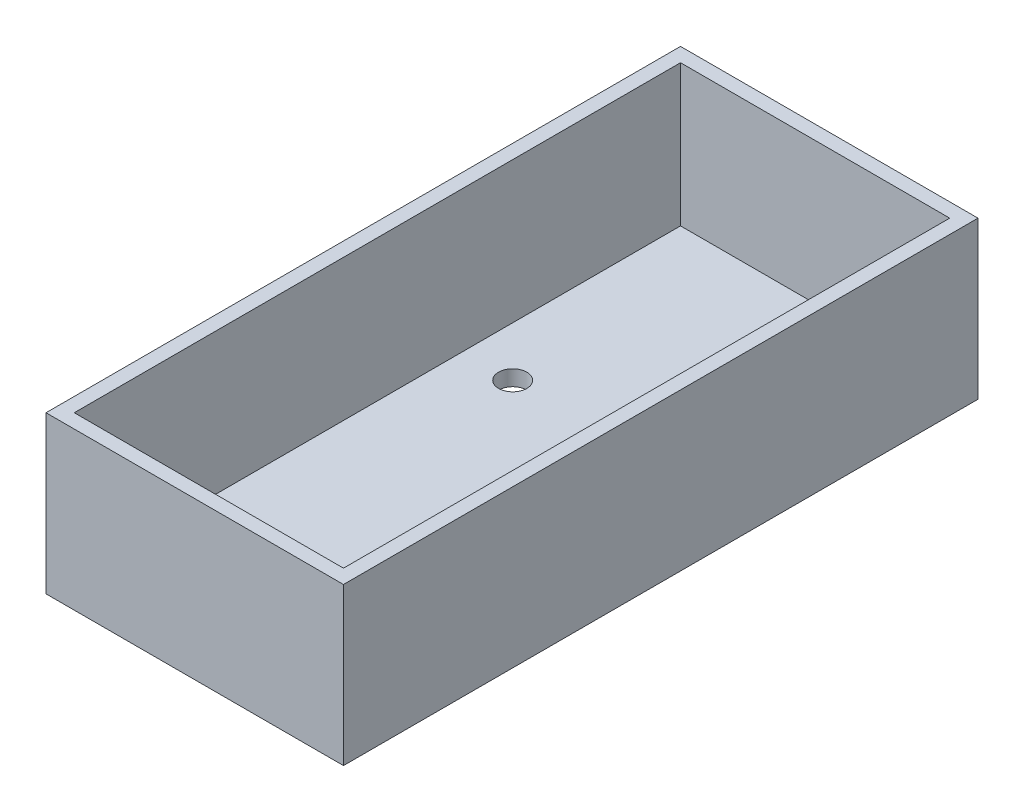
SolidWorks part; units mm, degrees
ref_plane "정면" through (0, 0, 0) normal (0, 0, 1) x (1, 0, 0)
ref_plane "윗면" through (0, 0, 0) normal (0, 1, 0) x (1, 0, 0)
ref_plane "우측면" through (0, 0, 0) normal (1, 0, 0) x (0, 0, -1)
sketch "스케치1" plane through (0, 0, 0) normal (0, 1, 0) x (1, 0, 0)
  line L1 (21.05, -44.9) -> (-21.05, -44.9)
  line L2 (21.05, -44.9) -> (21.05, 44.9)
  line L3 (21.05, 44.9) -> (-21.05, 44.9)
  line L4 (-21.05, -44.9) -> (-21.05, 44.9)
  point P5 (21.05, 0)
  point P8 (0, 44.9)
  dimension "D1" = 89.8
  dimension "D2" = 42.1
extrude "보스-돌출1" add sketch "스케치1" along normal blind 22.2
sketch "스케치2" plane through (0, 22.2, 0) normal (0, 1, 0) x (1, 0, 0)
  line L0 (-21.05, 44.9) -> (-21.05, -44.9) construction
  line L1 (-19.05, 42.9) -> (19.05, 42.9)
  line L2 (-19.05, 42.9) -> (-19.05, -42.9)
  line L3 (-19.05, -42.9) -> (19.05, -42.9)
  line L4 (19.05, 42.9) -> (19.05, -42.9)
  line L5 (-19.05, 42.9) -> (19.05, -42.9) construction
  line L6 (-19.05, -42.9) -> (19.05, 42.9) construction
  line L7 (21.05, 44.9) -> (-21.05, 44.9) construction
  point P0 (0, 0)
  dimension "D1" = 2
  dimension "D2" = 2
extrude "컷-돌출1" cut sketch "스케치2" against normal blind 20
sketch "스케치3" plane through (0, 2.2, 0) normal (0, 1, 0) x (1, 0, 0)
  line L0 (-21.05, -44.9) -> (21.05, -44.9) construction
  line L1 (-12, 12.1) -> (12, 12.1) construction
  line L2 (-12, 12.1) -> (-12, -27.9) construction
  line L3 (-12, -27.9) -> (12, -27.9) construction
  line L4 (12, 12.1) -> (12, -27.9) construction
  line L5 (-12, 12.1) -> (12, -27.9) construction
  line L6 (-12, -27.9) -> (12, 12.1) construction
  circle A0 centre (-12, -27.9) radius 2
  circle A1 centre (-12, 12.1) radius 2
  circle A2 centre (12, 12.1) radius 2
  circle A3 centre (12, -27.9) radius 2
  point P0 (0, -7.9)
  dimension "D4" = 4
  dimension "D5" = 4
  dimension "D1" = 40
  dimension "D2" = 24
  dimension "D3" = 17
extrude "컷-돌출2" cut sketch "스케치3" against normal through all
